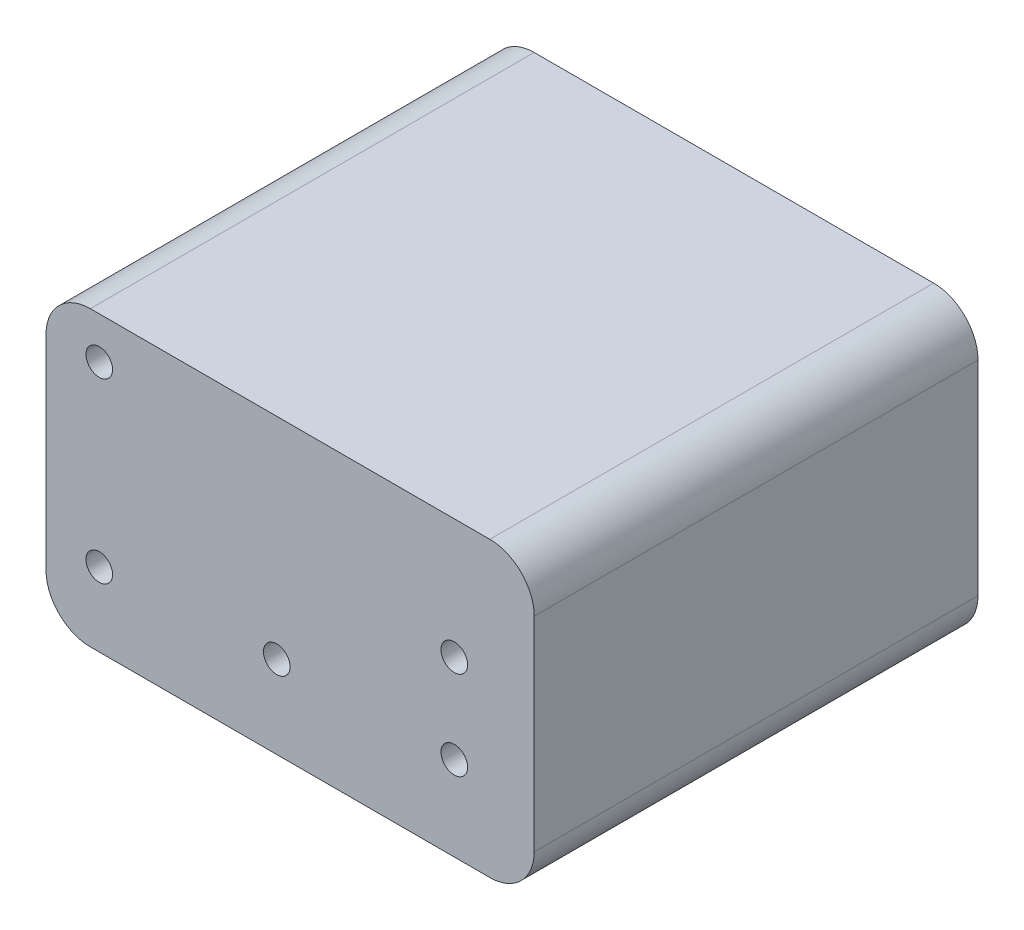
SolidWorks part; units mm, degrees
ref_plane "Plan de face" through (0, 0, 0) normal (0, 0, 1) x (1, 0, 0)
ref_plane "Plan de dessus" through (0, 0, 0) normal (0, 1, 0) x (1, 0, 0)
ref_plane "Plan de droite" through (0, 0, 0) normal (1, 0, 0) x (0, 0, -1)
sketch "Esquisse1" plane through (0, 0, 0) normal (0, 0, 1) x (1, 0, 0)
  line L1 (0, 0) -> (-55, 0)
  line L2 (0, 0) -> (0, 33)
  line L3 (0, 33) -> (-55, 33)
  line L4 (-55, 0) -> (-55, 33)
  dimension "D2" = 55
  dimension "D1" = 33
extrude "Boss.-Extru.1" add sketch "Esquisse1" along normal blind 50
sketch "Esquisse2" plane through (0, 0, 0) normal (0, 0, 1) x (1, 0, 0)
  line L6 (-38, 29) -> (-16, 29)
  line L7 (-38, 4) -> (-16, 4)
  line L8 (-55, 0) -> (0, 0) construction
  line L10 (0, 0) -> (0, 33) construction
  arc A3 (-38, 29) -> (-38, 4) centre (-38, 16.5) ccw
  arc A4 (-16, 4) -> (-16, 29) centre (-16, 16.5) ccw
  dimension "D3" = 4
  dimension "D7" = 16
  dimension "D5" = 22
  dimension "D6" = 25
extrude "Enlèv. mat.-Extru.2" cut sketch "Esquisse2" along normal blind 45
fillet "Congé1" radius 5 4 edges at (-55, 33, 25) (-55, 0, 25) (0, 0, 25) (0, 33, 25)
sketch "Esquisse3" plane through (0, 0, 50) normal (0, 0, 1) x (1, 0, 0)
  circle A0 centre (-29, 9.3) radius 1.5
  circle A1 centre (-9, 19.5) radius 1.5
  circle A3 centre (-9, 9.5) radius 1.5
  dimension "D1" = 3
  dimension "D2" = 3
  dimension "D3" = 3
extrude "Enlèv. mat.-Extru.3" cut sketch "Esquisse3" against normal blind 10
sketch "Esquisse4" plane through (0, 0, 45) normal (0, 0, -1) x (-1, 0, 0)
  line L0 (16, 29) -> (38, 29) construction
  line L1 (27.3546, 6.45) -> (30.6454, 6.45)
  line L2 (30.6454, 6.45) -> (32.2909, 9.3)
  line L3 (32.2909, 9.3) -> (30.6454, 12.15)
  line L4 (30.6454, 12.15) -> (27.3546, 12.15)
  line L5 (27.3546, 12.15) -> (25.7091, 9.3)
  line L6 (25.7091, 9.3) -> (27.3546, 6.45)
  line L7 (7.3546, 6.65) -> (10.6454, 6.65)
  line L8 (10.6454, 6.65) -> (12.2909, 9.5)
  line L9 (12.2909, 9.5) -> (10.6454, 12.35)
  line L10 (10.6454, 12.35) -> (7.3546, 12.35)
  line L11 (7.3546, 12.35) -> (5.7091, 9.5)
  line L12 (5.7091, 9.5) -> (7.3546, 6.65)
  line L13 (7.3546, 16.65) -> (10.6454, 16.65)
  line L14 (10.6454, 16.65) -> (12.2909, 19.5)
  line L15 (12.2909, 19.5) -> (10.6454, 22.35)
  line L16 (10.6454, 22.35) -> (7.3546, 22.35)
  line L17 (7.3546, 22.35) -> (5.7091, 19.5)
  line L18 (5.7091, 19.5) -> (7.3546, 16.65)
  circle A0 centre (29, 9.3) radius 2.85 construction
  circle A1 centre (9, 9.5) radius 2.85 construction
  circle A2 centre (9, 19.5) radius 2.85 construction
  point P19 (9, 6.65)
  point P28 (9, 22.35)
  dimension "D1" = 5.7
  dimension "D2" = 5.7
  dimension "D3" = 5.7
extrude "Enlèv. mat.-Extru.4" cut sketch "Esquisse4" against normal blind 2
sketch "Esquisse5" plane through (0, 0, 50) normal (0, 0, 1) x (1, 0, 0)
  circle A0 centre (-49, 28.3) radius 1.5
  circle A1 centre (-49, 8.3) radius 1.5
  dimension "D1" = 3
  dimension "D2" = 3
extrude "Enlèv. mat.-Extru.5" cut sketch "Esquisse5" against normal blind 4
sketch "Esquisse6" plane through (0, 0, 46) normal (0, 0, 1) x (1, 0, 0)
  circle A0 centre (-49, 28.3) radius 1.5
  circle A1 centre (-49, 8.3) radius 1.5
  dimension "D1" = 3
  dimension "D2" = 3
extrude "Enlèv. mat.-Extru.7" cut sketch "Esquisse6" against normal blind 4
